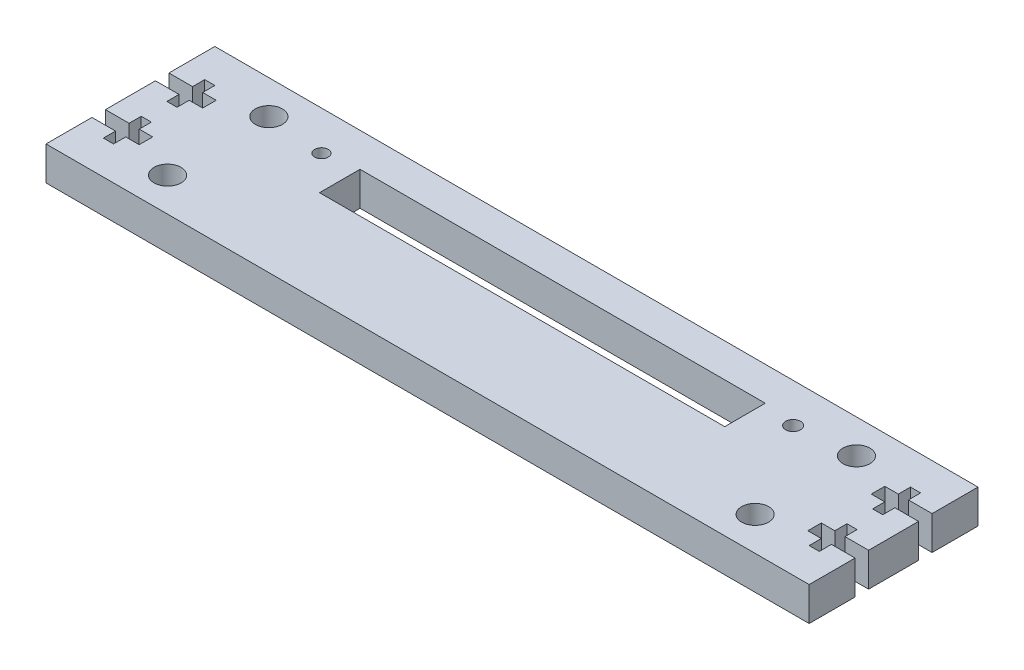
SolidWorks part; units mm, degrees
material "Acrílico (médio-alto impacto)"
ref_plane "Plano frontal" through (0, 0, 0) normal (0, 0, 1) x (1, 0, 0)
ref_plane "Plano superior" through (0, 0, 0) normal (0, 1, 0) x (1, 0, 0)
ref_plane "Plano direito" through (0, 0, 0) normal (1, 0, 0) x (0, 0, -1)
sketch "Esboço1" plane through (0, 0, 0) normal (0, 1, 0) x (1, 0, 0)
  line L1 (-47.2683, 18.484) -> (65.7317, 18.484)
  line L2 (-47.2683, 18.484) -> (-47.2683, -6.516)
  line L3 (-47.2683, -6.516) -> (65.7317, -6.516)
  line L4 (65.7317, 18.484) -> (65.7317, -6.516)
  dimension "D1" = 25
extrude "Ressalto-extrusão1" add sketch "Esboço1" along normal blind 5
sketch "Esboço2" plane through (0, 5, 0) normal (0, 1, 0) x (1, 0, 0)
  line L0 (65.7317, -6.516) -> (65.7317, 18.484) construction
  line L1 (65.7317, 0.284) -> (62.2317, 0.284)
  line L2 (65.7317, 0.284) -> (65.7317, 2.284)
  line L3 (65.7317, 2.284) -> (62.2317, 2.284)
  line L4 (60.7317, 4.084) -> (60.7317, 2.284)
  line L5 (60.7317, 0.284) -> (60.7317, -1.516)
  line L6 (62.2317, 2.284) -> (62.2317, 4.084)
  line L7 (60.7317, -1.516) -> (62.2317, -1.516)
  line L8 (60.7317, 2.284) -> (58.7317, 2.284)
  line L9 (60.7317, 4.084) -> (62.2317, 4.084)
  line L10 (62.2317, -1.516) -> (62.2317, 0.284)
  line L11 (65.7317, 9.684) -> (62.2317, 9.684)
  line L12 (60.7317, 0.284) -> (58.7317, 0.284)
  line L13 (58.7317, 2.284) -> (58.7317, 0.284)
  line L14 (62.2317, 9.684) -> (62.2317, 7.884)
  line L15 (62.2317, 7.884) -> (60.7317, 7.884)
  line L16 (60.7317, 7.884) -> (60.7317, 9.684)
  line L17 (60.7317, 9.684) -> (58.7317, 9.684)
  line L18 (-47.2683, -6.516) -> (65.7317, -6.516) construction
  line L19 (58.7317, 9.684) -> (58.7317, 11.684)
  line L20 (58.7317, 11.684) -> (60.7317, 11.684)
  line L21 (60.7317, 11.684) -> (60.7317, 13.484)
  line L22 (60.7317, 13.484) -> (62.2317, 13.484)
  line L23 (62.2317, 13.484) -> (62.2317, 11.684)
  line L24 (62.2317, 11.684) -> (65.7317, 11.684)
  line L25 (65.7317, 18.484) -> (-47.2683, 18.484) construction
  line L26 (65.7317, 11.684) -> (65.7317, 9.684)
  point P30 (0, 0)
  dimension "D1" = 6.8
  dimension "D2" = 1.8
  dimension "D3" = 1.8
  dimension "D4" = 3.5
  dimension "D5" = 2
  dimension "D6" = 1.8
  dimension "D7" = 6.8
  dimension "D8" = 2
  dimension "D9" = 1.8
  dimension "D10" = 1.8
  dimension "D11" = 1.8
  dimension "D12" = 2
extrude "Corte-extrusão1" cut sketch "Esboço2" against normal blind 5
sketch "Esboço4" plane through (0, 5, 0) normal (0, 1, 0) x (1, 0, 0)
  line L0 (-47.2683, 18.484) -> (-47.2683, -6.516) construction
  line L1 (65.7317, 18.484) -> (-47.2683, 18.484) construction
  line L2 (65.7317, 2.284) -> (65.7317, 9.684) construction
  circle A0 centre (-25.6883, 12.684) radius 1
  circle A1 centre (44.1517, 12.684) radius 1.1
  dimension "D1" = 21.58
  dimension "D2" = 5.8
  dimension "D3" = 21.58
extrude "Corte-extrusão2" cut sketch "Esboço4" against normal blind 76
sketch "Esboço5" plane through (0, 5, 0) normal (0, 1, 0) x (1, 0, 0)
  line L0 (-47.2683, -6.516) -> (65.7317, -6.516) construction
  line L1 (65.7317, 2.284) -> (65.7317, 9.684) construction
  line L2 (65.7317, 18.484) -> (-47.2683, 18.484) construction
  line L3 (-47.2683, 18.484) -> (-47.2683, -6.516) construction
  circle A0 centre (-34.2683, 13.484) radius 2
  circle A1 centre (-34.2683, -1.516) radius 2
  circle A2 centre (52.7317, 13.484) radius 2
  circle A3 centre (52.7317, -1.516) radius 2
  dimension "D1" = 5
  dimension "D2" = 13
  dimension "D3" = 13
  dimension "D4" = 5
  dimension "D5" = 5
  dimension "D6" = 13
  dimension "D7" = 13
  dimension "D8" = 5
extrude "Corte-extrusão3" cut sketch "Esboço5" against normal blind 10
sketch "Esboço6" plane through (0, 5, 0) normal (0, 1, 0) x (1, 0, 0)
  line L0 (65.7317, 18.484) -> (-47.2683, 18.484) construction
  line L1 (39.2317, 13.484) -> (9.2317, 13.484)
  line L2 (39.2317, 13.484) -> (39.2317, 7.484)
  line L3 (39.2317, 7.484) -> (9.2317, 7.484)
  line L4 (9.2317, 13.484) -> (9.2317, 7.484)
  dimension "D1" = 5
  dimension "D2" = 6
  dimension "D3" = 30
extrude "Corte-extrusão4" cut sketch "Esboço6" against normal blind 10
ref_plane "Plano1" through (9.2317, 0, 0) normal (1, 0, 0) x (0, 0, -1)
mirror "Espelhar1" about plane through (9.2317, 0, 0) normal (1, 0, 0) of "Corte-extrusão4", "Corte-extrusão1"
